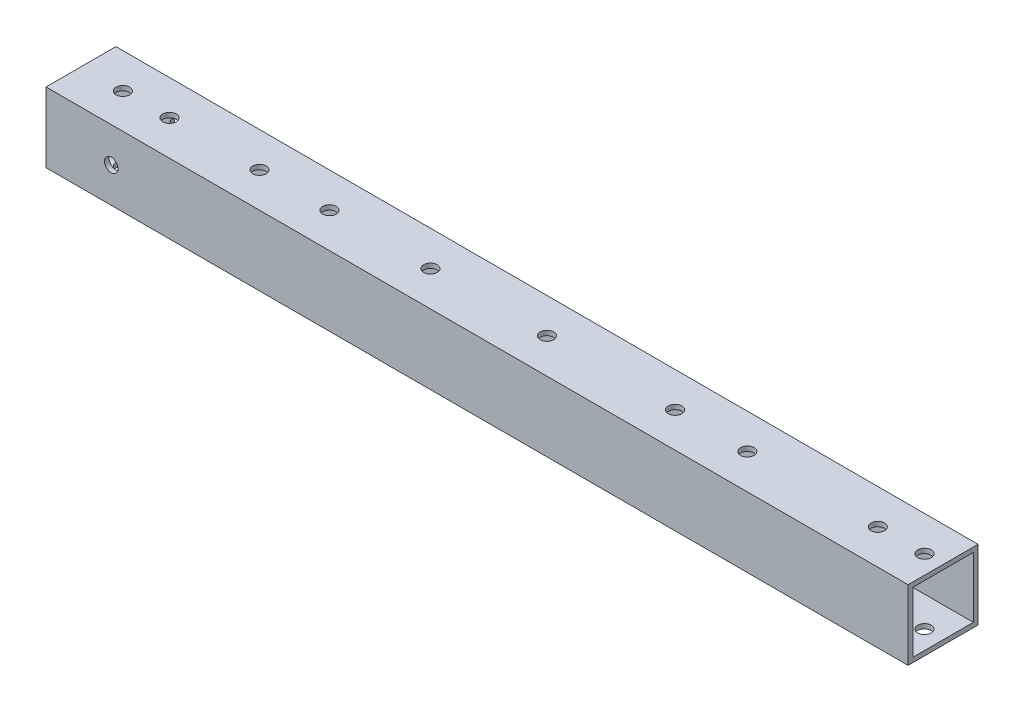
SolidWorks part; units mm, degrees
material "Thornel Mat VMA"
ref_plane "前视基准面" through (0, 0, 0) normal (0, 0, 1) x (1, 0, 0)
ref_plane "上视基准面" through (0, 0, 0) normal (0, 1, 0) x (1, 0, 0)
ref_plane "右视基准面" through (0, 0, 0) normal (1, 0, 0) x (0, 0, -1)
other "Configuration Table"
sketch "草图1" plane through (0, 0, 0) normal (1, 0, 0) x (0, 0, -1)
  line L0 (-6.5, -6.5) -> (-6.5, 6.5)
  line L1 (-7.5, -7.5) -> (7.5, -7.5)
  line L2 (-7.5, -7.5) -> (-7.5, 7.5)
  line L3 (-7.5, 7.5) -> (7.5, 7.5)
  line L4 (7.5, -7.5) -> (7.5, 7.5)
  line L5 (-7.5, -7.5) -> (7.5, 7.5) construction
  line L6 (-7.5, 7.5) -> (7.5, -7.5) construction
  line L7 (-6.5, 6.5) -> (6.5, 6.5)
  line L8 (6.5, -6.5) -> (6.5, 6.5)
  line L9 (-6.5, -6.5) -> (6.5, -6.5)
  point P0 (0, 0)
  dimension "D1" = 15
  dimension "D2" = 15
  dimension "D3" = 1
extrude "凸台-拉伸1" add sketch "草图1" along normal blind 185
sketch "草图2" plane through (0, -7.5, 0) normal (0, -1, 0) x (1, 0, 0)
  circle A0 centre (181, 0) radius 1.45 construction
  circle A1 centre (171, 0) radius 1.45 construction
  circle A2 centre (127.5, 0) radius 1.45 construction
  circle A3 centre (100, 0) radius 1.45 construction
  circle A4 centre (75, 0) radius 1.45 construction
  circle A5 centre (19, 0) radius 1.45 construction
  circle A6 centre (9, 0) radius 1.45 construction
  circle A7 centre (181, 0) radius 1.45
  circle A8 centre (171, 0) radius 1.45
  circle A9 centre (127.5, 0) radius 1.45
  circle A10 centre (100, 0) radius 1.45
  circle A11 centre (75, 0) radius 1.45
  circle A12 centre (19, 0) radius 1.45
  circle A13 centre (9, 0) radius 1.45
  circle A14 centre (143, 0) radius 1.45 construction
  circle A15 centre (143, 0) radius 1.45
  circle A16 centre (38.3229, 0) radius 1.45 construction
  circle A17 centre (53.3229, 0) radius 1.45 construction
  circle A18 centre (38.3229, 0) radius 1.45
  circle A19 centre (53.3229, 0) radius 1.45
extrude "切除-拉伸1" cut sketch "草图2" against normal through all
sketch "草图3" plane through (0, 0, 7.5) normal (0, 0, 1) x (1, 0, 0)
  circle A0 centre (14, 0) radius 1.45 construction
  circle A1 centre (14, 0) radius 1.45
extrude "切除-拉伸2" cut sketch "草图3" against normal through all
